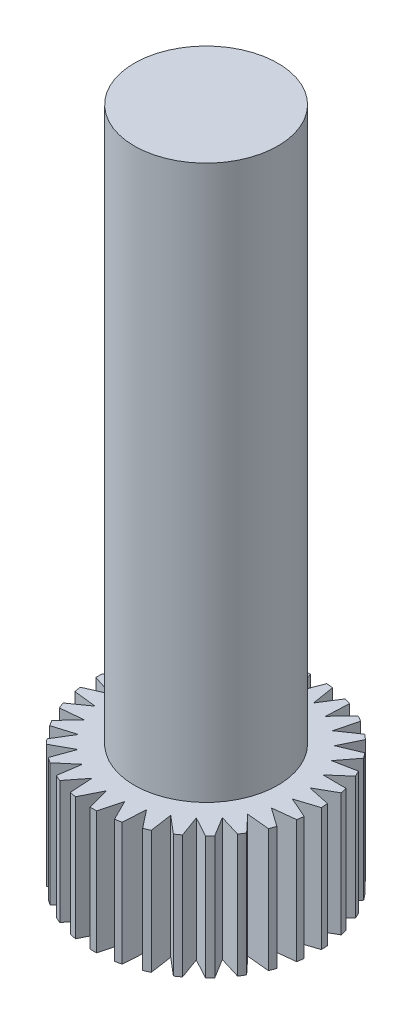
SolidWorks part; units mm, degrees
ref_plane "Спереди" through (0, 0, 0) normal (0, 0, 1) x (1, 0, 0)
ref_plane "Сверху" through (0, 0, 0) normal (0, 1, 0) x (1, 0, 0)
ref_plane "Справа" through (0, 0, 0) normal (1, 0, 0) x (0, 0, -1)
sketch "Эскиз1" plane through (0, 0, 0) normal (0, 1, 0) x (1, 0, 0)
  circle A0 centre (0, 0) radius 5.5
extrude "Вытянуть1" add sketch "Эскиз1" along normal blind 6
sketch "Эскиз2" plane through (0, 0, 0) normal (0, 1, 0) x (1, 0, 0)
  line L0 (0, 0) -> (0, 8.786) construction
  line L1 (-0.5, 5.7588) -> (0.5, 5.7588)
  line L2 (-0.5, 5.7588) -> (0, 4.4371)
  line L3 (0, 4.4371) -> (0.5, 5.7588)
  line L4 (0.6695, 5.7416) -> (0.8932, 4.3463)
  line L5 (0.6695, 5.7416) -> (1.649, 5.5403)
  line L6 (0.8932, 4.3463) -> (1.649, 5.5403)
  line L7 (1.8115, 5.4893) -> (1.7498, 4.0775)
  line L8 (1.8115, 5.4893) -> (2.7305, 5.0949)
  line L9 (1.7498, 4.0775) -> (2.7305, 5.0949)
  line L10 (2.8794, 5.0123) -> (2.5348, 3.6418)
  line L11 (2.8794, 5.0123) -> (3.7002, 4.441)
  line L12 (2.5348, 3.6418) -> (3.7002, 4.441)
  line L13 (3.8295, 4.33) -> (3.216, 3.057)
  line L14 (3.8295, 4.33) -> (4.5184, 3.6052)
  line L15 (3.216, 3.057) -> (4.5184, 3.6052)
  line L16 (4.6227, 3.4705) -> (3.7655, 2.3471)
  line L17 (4.6227, 3.4705) -> (5.1517, 2.6219)
  line L18 (3.7655, 2.3471) -> (5.1517, 2.6219)
  line L19 (5.2267, 2.4689) -> (4.1609, 1.541)
  line L20 (5.2267, 2.4689) -> (5.574, 1.5312)
  line L21 (4.1609, 1.541) -> (5.574, 1.5312)
  line L22 (5.6167, 1.3663) -> (4.3859, 0.6719)
  line L23 (5.6167, 1.3663) -> (5.7681, 0.3778)
  line L24 (4.3859, 0.6719) -> (5.7681, 0.3778)
  line L25 (5.7768, 0.2077) -> (4.4314, -0.2247)
  line L26 (5.7768, 0.2077) -> (5.7261, -0.791)
  line L27 (4.4314, -0.2247) -> (5.7261, -0.791)
  line L28 (5.7003, -0.9594) -> (4.2954, -1.1122)
  line L29 (5.7003, -0.9594) -> (5.4497, -1.9275)
  line L30 (4.2954, -1.1122) -> (5.4497, -1.9275)
  line L31 (5.3905, -2.0872) -> (3.9836, -1.9541)
  line L32 (5.3905, -2.0872) -> (4.9501, -2.9851)
  line L33 (3.9836, -1.9541) -> (4.9501, -2.9851)
  line L34 (4.86, -3.1296) -> (3.5087, -2.716)
  line L35 (4.86, -3.1296) -> (4.2479, -3.9204)
  line L36 (3.5087, -2.716) -> (4.2479, -3.9204)
  line L37 (4.1305, -4.0439) -> (2.8902, -3.3667)
  line L38 (4.1305, -4.0439) -> (3.3718, -4.6952)
  line L39 (2.8902, -3.3667) -> (3.3718, -4.6952)
  line L40 (3.2319, -4.7926) -> (2.1533, -3.8796)
  line L41 (3.2319, -4.7926) -> (2.3576, -5.2779)
  line L42 (2.1533, -3.8796) -> (2.3576, -5.2779)
  line L43 (2.201, -5.345) -> (1.3283, -4.2336)
  line L44 (2.201, -5.345) -> (1.2469, -5.6444)
  line L45 (1.3283, -4.2336) -> (1.2469, -5.6444)
  line L46 (1.08, -5.6787) -> (0.4489, -4.4143)
  line L47 (1.08, -5.6787) -> (0.0852, -5.7799)
  line L48 (0.4489, -4.4143) -> (0.0852, -5.7799)
  line L49 (-0.0852, -5.7799) -> (-0.4489, -4.4143)
  line L50 (-0.0852, -5.7799) -> (-1.08, -5.6787)
  line L51 (-0.4489, -4.4143) -> (-1.08, -5.6787)
  line L52 (-1.2469, -5.6444) -> (-1.3283, -4.2336)
  line L53 (-1.2469, -5.6444) -> (-2.201, -5.345)
  line L54 (-1.3283, -4.2336) -> (-2.201, -5.345)
  line L55 (-2.3576, -5.2779) -> (-2.1533, -3.8796)
  line L56 (-2.3576, -5.2779) -> (-3.2319, -4.7926)
  line L57 (-2.1533, -3.8796) -> (-3.2319, -4.7926)
  line L58 (-3.3718, -4.6952) -> (-2.8902, -3.3667)
  line L59 (-3.3718, -4.6952) -> (-4.1305, -4.0439)
  line L60 (-2.8902, -3.3667) -> (-4.1305, -4.0439)
  line L61 (-4.2479, -3.9204) -> (-3.5087, -2.716)
  line L62 (-4.2479, -3.9204) -> (-4.86, -3.1296)
  line L63 (-3.5087, -2.716) -> (-4.86, -3.1296)
  line L64 (-4.9501, -2.9851) -> (-3.9836, -1.9541)
  line L65 (-4.9501, -2.9851) -> (-5.3905, -2.0872)
  line L66 (-3.9836, -1.9541) -> (-5.3905, -2.0872)
  line L67 (-5.4497, -1.9275) -> (-4.2954, -1.1122)
  line L68 (-5.4497, -1.9275) -> (-5.7003, -0.9594)
  line L69 (-4.2954, -1.1122) -> (-5.7003, -0.9594)
  line L70 (-5.7261, -0.791) -> (-4.4314, -0.2247)
  line L71 (-5.7261, -0.791) -> (-5.7768, 0.2077)
  line L72 (-4.4314, -0.2247) -> (-5.7768, 0.2077)
  line L73 (-5.7681, 0.3778) -> (-4.3859, 0.6719)
  line L74 (-5.7681, 0.3778) -> (-5.6167, 1.3663)
  line L75 (-4.3859, 0.6719) -> (-5.6167, 1.3663)
  line L76 (-5.574, 1.5312) -> (-4.1609, 1.541)
  line L77 (-5.574, 1.5312) -> (-5.2267, 2.4689)
  line L78 (-4.1609, 1.541) -> (-5.2267, 2.4689)
  line L79 (-5.1517, 2.6219) -> (-3.7655, 2.3471)
  line L80 (-5.1517, 2.6219) -> (-4.6227, 3.4705)
  line L81 (-3.7655, 2.3471) -> (-4.6227, 3.4705)
  line L82 (-4.5184, 3.6052) -> (-3.216, 3.057)
  line L83 (-4.5184, 3.6052) -> (-3.8295, 4.33)
  line L84 (-3.216, 3.057) -> (-3.8295, 4.33)
  line L85 (-3.7002, 4.441) -> (-2.5348, 3.6418)
  line L86 (-3.7002, 4.441) -> (-2.8794, 5.0123)
  line L87 (-2.5348, 3.6418) -> (-2.8794, 5.0123)
  line L88 (-2.7305, 5.0949) -> (-1.7498, 4.0775)
  line L89 (-2.7305, 5.0949) -> (-1.8115, 5.4893)
  line L90 (-1.7498, 4.0775) -> (-1.8115, 5.4893)
  line L91 (-1.649, 5.5403) -> (-0.8932, 4.3463)
  line L92 (-1.649, 5.5403) -> (-0.6695, 5.7416)
  line L93 (-0.8932, 4.3463) -> (-0.6695, 5.7416)
  dimension "D1" = 0.5
  dimension "D2" = 0.5
extrude "Вытянуть4" cut sketch "Эскиз2" along normal through all
sketch "Эскиз3" plane through (0, 6, 0) normal (0, 1, 0) x (-1, 0, 0)
  circle A0 centre (0, 0) radius 3.5
extrude "Вытянуть5" add sketch "Эскиз3" along normal blind 27
